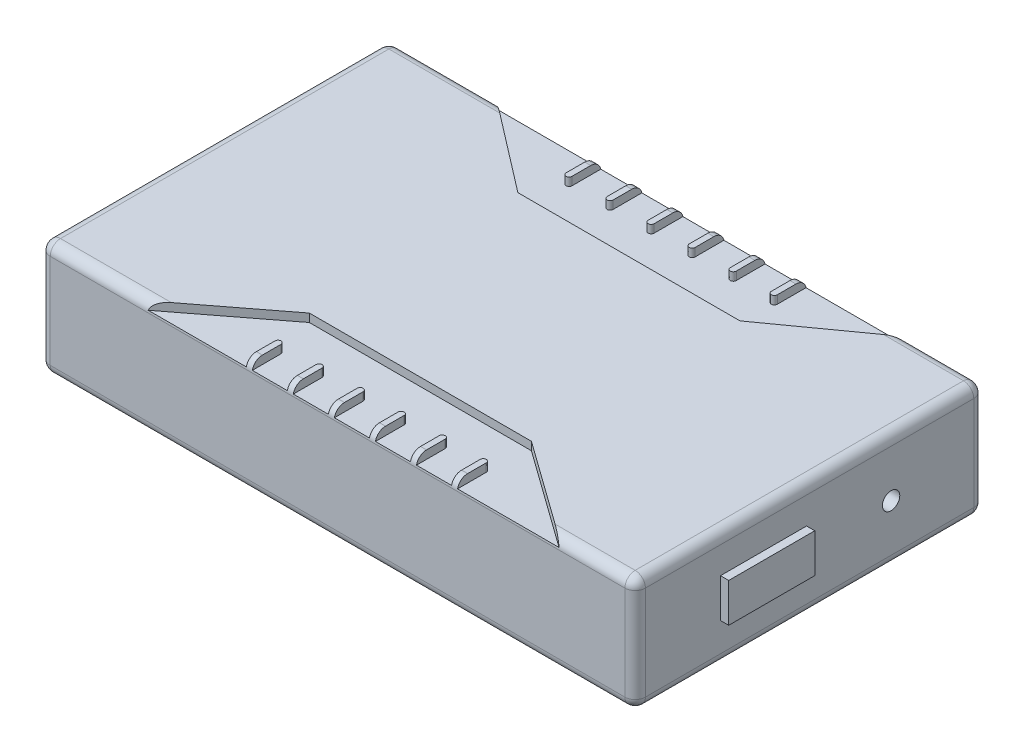
SolidWorks part; units mm, degrees
ref_plane "Front Plane" through (0, 0, 0) normal (0, 0, 1) x (1, 0, 0)
ref_plane "Top Plane" through (0, 0, 0) normal (0, 1, 0) x (1, 0, 0)
ref_plane "Right Plane" through (0, 0, 0) normal (1, 0, 0) x (0, 0, -1)
sketch "Sketch2" plane through (0, 0, 0) normal (0, 1, 0) x (1, 0, 0)
  line L1 (0, 0) -> (145, 0)
  line L2 (0, 0) -> (0, 85)
  line L3 (0, 85) -> (145, 85)
  line L4 (145, 0) -> (145, 85)
  dimension "D1" = 85
  dimension "D2" = 145
extrude "Boss-Extrude1" add sketch "Sketch2" along normal blind 28
fillet "Fillet1" radius 2.5 12 edges at (0, 14, -85) (0, 14, 0) (145, 14, 0) (145, 14, -85) (72.5, 0, 0) (145, 0, -42.5) (72.5, 0, -85) (0, 0, -42.5) (72.5, 28, -85) (145, 28, -42.5) (72.5, 28, 0) (0, 28, -42.5)
sketch "Sketch3" plane through (145, 0, 0) normal (1, 0, 0) x (0, 0, -1)
  circle A0 centre (62.3559, 14.0208) radius 2.1153
extrude "Cut-Extrude1" cut sketch "Sketch3" against normal blind 10 contours A0
sketch "Sketch4" plane through (145, 0, 0) normal (1, 0, 0) x (0, 0, -1)
  line L1 (20.7999, 18.9695) -> (41.7623, 18.9695)
  line L2 (20.7999, 18.9695) -> (20.7999, 9.5026)
  line L3 (20.7999, 9.5026) -> (41.7623, 9.5026)
  line L4 (41.7623, 18.9695) -> (41.7623, 9.5026)
extrude "Boss-Extrude2" add sketch "Sketch4" along normal blind 2
sketch "Sketch5" plane through (0, 28, 0) normal (0, 1, 0) x (1, 0, 0)
  line L0 (26.2545, 85) -> (48.5303, 67.9016)
  line L1 (2.5, 85) -> (142.5, 85) construction
  line L2 (48.5303, 67.9016) -> (102.6435, 67.9016)
  line L3 (102.6435, 67.9016) -> (126.477, 85)
  line L4 (26.2545, 85) -> (50.2195, 85)
  line L5 (50.2195, 85) -> (50.2195, 77.9553)
  line L6 (51.6786, 77.9553) -> (51.6786, 85)
  line L7 (61.6786, 77.9553) -> (61.6786, 85)
  line L8 (60.2195, 85) -> (60.2195, 77.9553)
  line L9 (71.6786, 77.9553) -> (71.6786, 85)
  line L10 (70.2195, 85) -> (70.2195, 77.9553)
  line L11 (81.6786, 77.9553) -> (81.6786, 85)
  line L12 (80.2195, 85) -> (80.2195, 77.9553)
  line L13 (91.6786, 77.9553) -> (91.6786, 85)
  line L14 (90.2195, 85) -> (90.2195, 77.9553)
  line L15 (101.6786, 77.9553) -> (101.6786, 85)
  line L16 (100.2195, 85) -> (100.2195, 77.9553)
  line L17 (51.6786, 85) -> (60.2195, 85)
  line L18 (61.6786, 85) -> (70.2195, 85)
  line L19 (71.6786, 85) -> (80.2195, 85)
  line L20 (81.6786, 85) -> (90.2195, 85)
  line L21 (91.6786, 85) -> (100.2195, 85)
  line L22 (101.6786, 85) -> (126.477, 85)
  line L23 (0, 42.5) -> (138.8824, 42.5) construction
  line L24 (0, 2.5) -> (0, 82.5) construction
  line L26 (101.6786, 0) -> (126.477, 0)
  line L27 (91.6786, 0) -> (100.2195, 0)
  line L28 (81.6786, 0) -> (90.2195, 0)
  line L29 (71.6786, 0) -> (80.2195, 0)
  line L30 (61.6786, 0) -> (70.2195, 0)
  line L31 (51.6786, 0) -> (60.2195, 0)
  line L32 (100.2195, 0) -> (100.2195, 7.0447)
  line L33 (101.6786, 7.0447) -> (101.6786, 0)
  line L34 (90.2195, 0) -> (90.2195, 7.0447)
  line L35 (91.6786, 7.0447) -> (91.6786, 0)
  line L36 (80.2195, 0) -> (80.2195, 7.0447)
  line L37 (81.6786, 7.0447) -> (81.6786, 0)
  line L38 (70.2195, 0) -> (70.2195, 7.0447)
  line L39 (71.6786, 7.0447) -> (71.6786, 0)
  line L40 (60.2195, 0) -> (60.2195, 7.0447)
  line L41 (61.6786, 7.0447) -> (61.6786, 0)
  line L42 (51.6786, 7.0447) -> (51.6786, 0)
  line L43 (50.2195, 0) -> (50.2195, 7.0447)
  line L44 (26.2545, 0) -> (50.2195, 0)
  line L45 (102.6435, 17.0984) -> (126.477, 0)
  line L46 (48.5303, 17.0984) -> (102.6435, 17.0984)
  line L47 (26.2545, 0) -> (48.5303, 17.0984)
  arc A0 (50.2195, 77.9553) -> (51.6786, 77.9553) centre (50.949, 77.9553) ccw
  arc A1 (60.2195, 77.9553) -> (61.6786, 77.9553) centre (60.949, 77.9553) ccw
  arc A2 (70.2195, 77.9553) -> (71.6786, 77.9553) centre (70.949, 77.9553) ccw
  arc A3 (80.2195, 77.9553) -> (81.6786, 77.9553) centre (80.949, 77.9553) ccw
  arc A4 (90.2195, 77.9553) -> (91.6786, 77.9553) centre (90.949, 77.9553) ccw
  arc A5 (100.2195, 77.9553) -> (101.6786, 77.9553) centre (100.949, 77.9553) ccw
  arc A6 (100.2195, 7.0447) -> (101.6786, 7.0447) centre (100.949, 7.0447) cw
  arc A7 (90.2195, 7.0447) -> (91.6786, 7.0447) centre (90.949, 7.0447) cw
  arc A8 (80.2195, 7.0447) -> (81.6786, 7.0447) centre (80.949, 7.0447) cw
  arc A9 (70.2195, 7.0447) -> (71.6786, 7.0447) centre (70.949, 7.0447) cw
  arc A10 (60.2195, 7.0447) -> (61.6786, 7.0447) centre (60.949, 7.0447) cw
  arc A11 (50.2195, 7.0447) -> (51.6786, 7.0447) centre (50.949, 7.0447) cw
  dimension "D1" = 6
extrude "Cut-Extrude2" cut sketch "Sketch5" against normal blind 2
